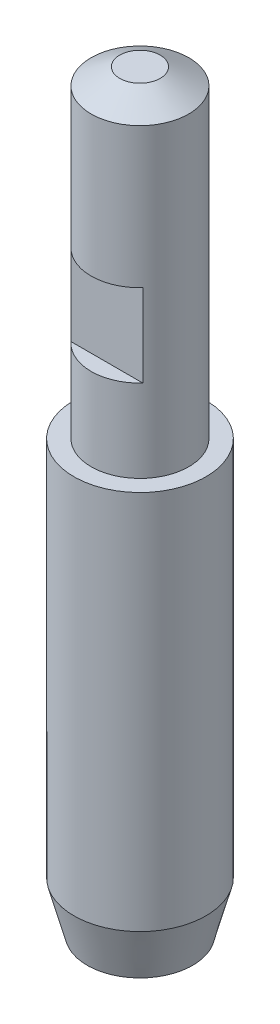
SolidWorks part; units mm, degrees
ref_plane "Face" through (0, 0, 0) normal (0, 0, 1) x (1, 0, 0)
ref_plane "Dessus" through (0, 0, 0) normal (0, 1, 0) x (1, 0, 0)
ref_plane "Droite" through (0, 0, 0) normal (1, 0, 0) x (0, 0, -1)
sketch "Esquisse1" plane through (0, 0, 0) normal (0, 0, 1) x (1, 0, 0)
  line L0 (0, 77.0952) -> (0, 76.2319) construction
  line L1 (0, 73.0948) -> (0, 56) construction
  line L2 (0, 30) -> (-3.1962, 30)
  line L3 (2.25, 30) -> (-2.25, 30) construction
  line L4 (-4, 33) -> (-3.1962, 30)
  line L5 (-4, 33) -> (-4, 56.0253)
  line L6 (-36.5881, 56.0253) -> (60, 56.0253) construction
  line L7 (-4, 56.0253) -> (-2.9559, 56.0253)
  line L9 (-2.9559, 56.0253) -> (-2.9559, 74.5253)
  line L10 (-2.9559, 74.5253) -> (-1.2239, 75.5253)
  line L11 (0, 30) -> (0, 75.5253)
  line L13 (0, 75.5253) -> (-1.2239, 75.5253)
  line L15 (0, 75.5253) -> (0, 19.458) construction
  dimension "D1" = 4
  dimension "D2" = 15
revolve "Révolution1" add sketch "Esquisse1" angle 360 about L0
sketch "Esquisse4" plane through (0, 30, 0) normal (0, -1, 0) x (1, 0, 0)
  circle A0 centre (0, 0) radius 1.6
extrude "Enlèv. mat.-Extru.1" cut sketch "Esquisse4" against normal blind 10
ref_plane "Plan1" through (0, 29.5, 0) normal (0, 1, 0) x (-1, 0, 0)
sketch "Esquisse7" plane through (0, 0, 0) normal (1, 0, 0) x (0, 0, -1)
  line L0 (0, 73.6087) -> (0, 58.8562) construction
  line L1 (-4.2323, 66.0253) -> (-2, 66.0253)
  line L2 (-4.2323, 66.0253) -> (-4.2323, 61.0253)
  line L3 (-4.2323, 61.0253) -> (-2, 61.0253)
  line L4 (-2, 66.0253) -> (-2, 61.0253)
  line L5 (0, 56.0253) -> (0, 74.5253) construction
  line L6 (4.2323, 66.0253) -> (2, 66.0253)
  line L7 (4.2323, 66.0253) -> (4.2323, 61.0253)
  line L8 (4.2323, 61.0253) -> (2, 61.0253)
  line L9 (2, 66.0253) -> (2, 61.0253)
  dimension "D1" = 2
  dimension "D2" = 5
extrude "Enlèv. mat.-Extru.3" cut sketch "Esquisse7" against normal mid plane 10
